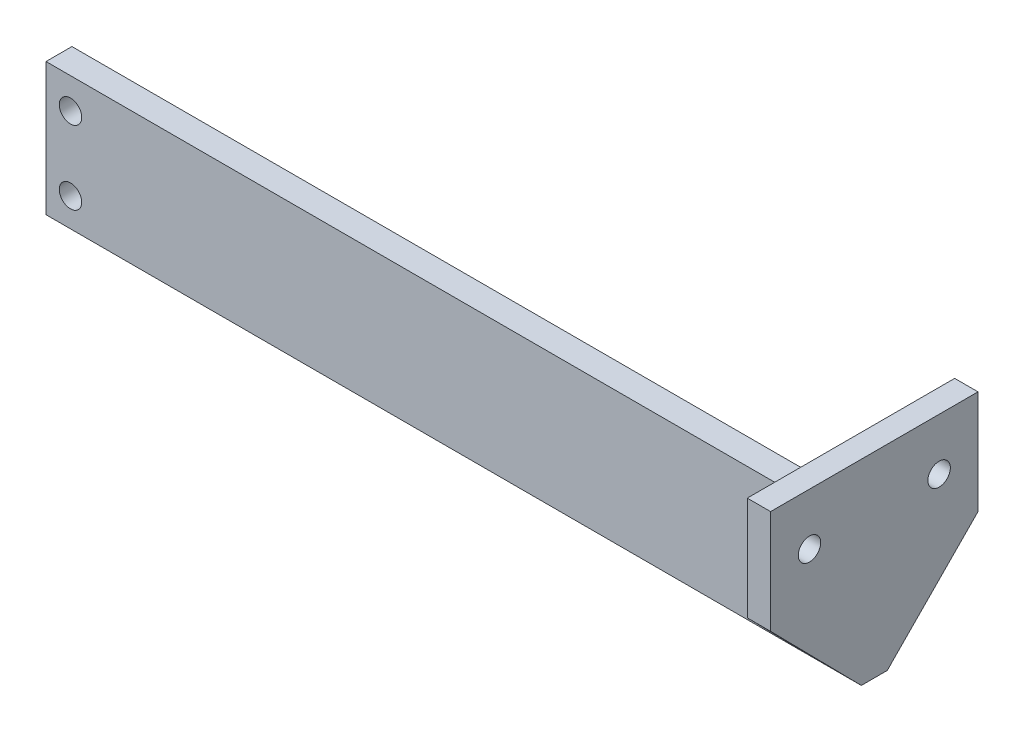
SolidWorks part; units mm, degrees
ref_plane "Front Plane" through (0, 0, 0) normal (0, 0, 1) x (1, 0, 0)
ref_plane "Top Plane" through (0, 0, 0) normal (0, 1, 0) x (1, 0, 0)
ref_plane "Right Plane" through (0, 0, 0) normal (1, 0, 0) x (0, 0, -1)
sketch "Sketch1" plane through (0, 0, 0) normal (0, 0, 1) x (1, 0, 0)
  line L1 (0, 0) -> (193.9764, 0)
  line L2 (0, 0) -> (0, 32.5)
  line L3 (0, 32.5) -> (193.9764, 32.5)
  line L4 (193.9764, 0) -> (193.9764, 32.5)
  dimension "D1" = 193.9764
  dimension "D2" = 32.5
extrude "Boss-Extrude1" add sketch "Sketch1" along normal blind 6.35
sketch "Sketch2" plane through (0, 0, 6.35) normal (0, 0, 1) x (1, 0, 0)
  line L0 (0, 32.5) -> (0, 0) construction
  line L1 (0, 0) -> (193.9764, 0) construction
  circle A0 centre (6, 25) radius 2.75
  circle A1 centre (6, 7) radius 2.75
  point P6 (0, 0)
  point P7 (0, 0)
  point P10 (0, 0)
  point P11 (0, 0)
  dimension "D1" = 5.5
  dimension "D2" = 6
  dimension "D3" = 18
  dimension "D4" = 25
extrude "Cut-Extrude1" cut sketch "Sketch2" against normal through all
sketch "Sketch3" plane through (193.9764, 0, 0) normal (1, 0, 0) x (0, 0, -1)
  line L0 (-3.175, 32.5) -> (-3.175, 39.5009) construction
  line L1 (-28.575, 22.594) -> (22.225, 22.594)
  line L2 (-28.575, 22.594) -> (-28.575, 39.5009)
  line L3 (-28.575, 39.5009) -> (22.225, 39.5009)
  line L4 (22.225, 22.594) -> (22.225, 39.5009)
  line L5 (-6.35, 32.5) -> (0, 32.5) construction
  line L7 (-28.575, 22.594) -> (-6.35, 0)
  line L8 (-6.35, 0) -> (0, 0)
  line L9 (22.225, 22.594) -> (0, 0)
  line L11 (-28.575, 39.5009) -> (22.225, 39.5009)
  line L12 (-28.575, 39.5009) -> (-28.575, 47.994)
  line L13 (-28.575, 47.994) -> (22.225, 47.994)
  line L14 (22.225, 39.5009) -> (22.225, 47.994)
  point P9 (-3.175, 39.5009)
  line M4 (0, 0) -> (0, 32.5)
  line M5 (0, 32.5) -> (-6.35, 32.5)
  line M6 (-6.35, 32.5) -> (-6.35, 0)
  line M7 (-6.35, 0) -> (0, 0)
  dimension "D1" = 25.4
  dimension "D2" = 50.8
  dimension "D3" = 15.494
extrude "Boss-Extrude2" add sketch "Sketch3" along normal blind 5.715 contours L1 L4 L3 L2 M6 M5 M4 | L1 L7 M6 | L1 M6 M4 M5 | L1 M6 M7 M4 | L9 L1 M4 | L3 L14 L13 L12 | L0 L3 L2 L1 M5 M6
sketch "Sketch4" plane through (199.6914, 0, 0) normal (1, 0, 0) x (0, 0, -1)
  line L0 (-28.575, 22.594) -> (-28.575, 47.994) construction
  line L1 (-28.575, 47.994) -> (22.225, 47.994) construction
  circle A0 centre (-19.05, 35.294) radius 2.75
  circle A1 centre (12.7, 35.294) radius 2.75
  point P4 (0, 0)
  point P7 (0, 0)
  dimension "D1" = 5.5
  dimension "D2" = 31.75
  dimension "D3" = 9.525
  dimension "D4" = 12.7
extrude "Cut-Extrude2" cut sketch "Sketch4" against normal through all
